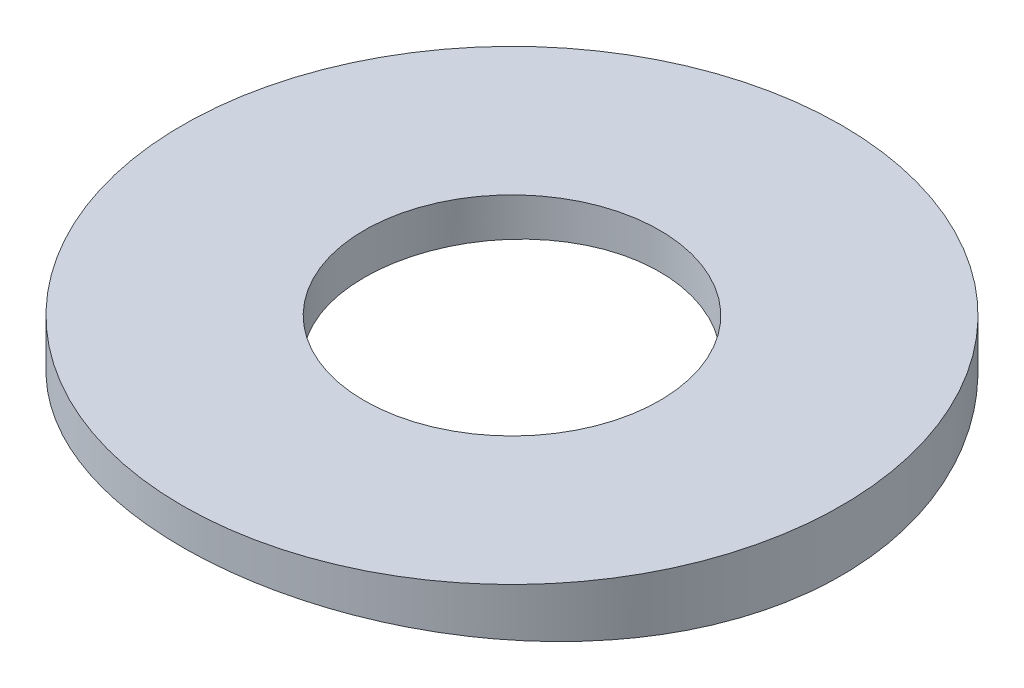
SolidWorks part; units mm, degrees
ref_plane "Front Plane" through (0, 0, 0) normal (1, 0, 0) x (0, 1, 0)
ref_plane "Top Plane" through (0, 0, 0) normal (0, 0, 1) x (0, 1, 0)
ref_plane "Right Plane" through (0, 0, 0) normal (0, 1, 0) x (-1, 0, 0)
sketch "Sketch1" plane through (0, 0, 0) normal (0, 0, 1) x (0, 1, 0)
  circle A0 centre (0, 0) radius 31
  dimension "D1" = 62
sketch "Sketch2" plane through (0, 0, 0) normal (0, 1, 0) x (-1, 0, 0)
  line L0 (31, 0) -> (-31, 0) construction
  circle A0 centre (0, 0) radius 4.575
  dimension "D1" = 9.15
extrude "Boss-Extrude1" add sketch "Sketch2" along normal blind 31.5
extrude "Cut-Extrude1" cut sketch "Sketch1" against normal through all both and the other way through all
sketch "Sketch3" plane through (0, 31.5, 0) normal (0, 1, 0) x (-1, 0, 0)
  circle A0 centre (0, 0) radius 2.05
  dimension "D1" = 4.1
extrude "Cut-Extrude2" cut sketch "Sketch3" against normal through all both and the other way through all
